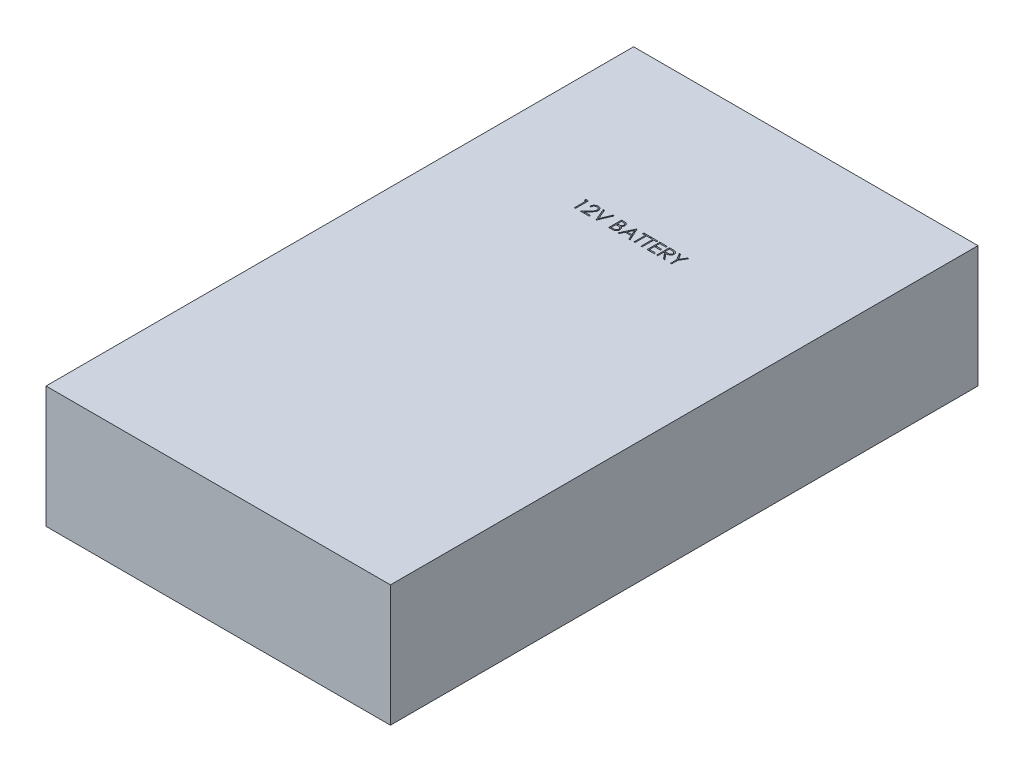
SolidWorks part; units mm, degrees
ref_plane "Front Plane" through (0, 0, 0) normal (0, 0, 1) x (1, 0, 0)
ref_plane "Top Plane" through (0, 0, 0) normal (0, 1, 0) x (1, 0, 0)
ref_plane "Right Plane" through (0, 0, 0) normal (1, 0, 0) x (0, 0, -1)
sketch "Sketch1" plane through (0, 0, 0) normal (0, 1, 0) x (1, 0, 0)
  line L1 (-42.5, -72.5) -> (42.5, -72.5)
  line L2 (-42.5, -72.5) -> (-42.5, 72.5)
  line L3 (-42.5, 72.5) -> (42.5, 72.5)
  line L4 (42.5, -72.5) -> (42.5, 72.5)
  line L5 (-42.5, -72.5) -> (42.5, 72.5) construction
  line L6 (-42.5, 72.5) -> (42.5, -72.5) construction
  point P0 (0, 0)
  dimension "D1" = 85
  dimension "D2" = 145
extrude "Boss-Extrude1" add sketch "Sketch1" along normal blind 30
sketch "Sketch2" plane through (0, 30, 0) normal (0, 1, 0) x (1, 0, 0)
  text T0 "12V BATTERY "
extrude "Cut-Extrude1" cut sketch "Sketch2" against normal blind 1
